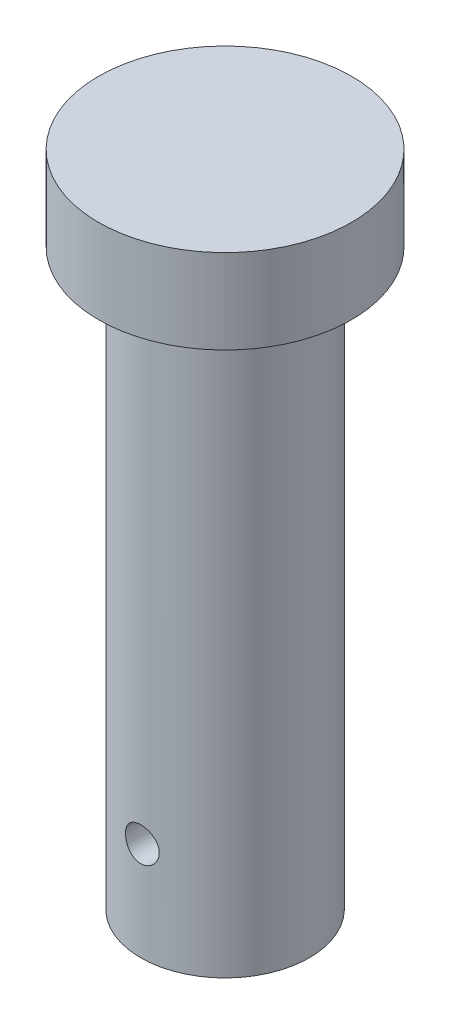
SolidWorks part; units mm, degrees
ref_plane "Front Plane" through (0, 0, 0) normal (0, 0, 1) x (1, 0, 0)
ref_plane "Top Plane" through (0, 0, 0) normal (0, 1, 0) x (1, 0, 0)
ref_plane "Right Plane" through (0, 0, 0) normal (1, 0, 0) x (0, 0, -1)
sketch "Sketch1" plane through (0, 0, 0) normal (0, 0, 1) x (1, 0, 0)
  line L0 (0, 0) -> (15, 0)
  line L1 (15, 0) -> (15, 102)
  line L2 (15, 102) -> (22.5, 102)
  line L3 (22.5, 102) -> (22.5, 117)
  line L4 (22.5, 117) -> (0, 117)
  line L5 (0, 117) -> (0, 0)
  dimension "D1" = 15
  dimension "D2" = 102
  dimension "D3" = 15
  dimension "D4" = 22.5
revolve "Revolve1" add sketch "Sketch1" angle 360 about L5
sketch "Sketch2" plane through (0, 0, 0) normal (0, 0, 1) x (1, 0, 0)
  circle A0 centre (0, 17.5) radius 3
  dimension "D1" = 6
  dimension "D2" = 17.5
extrude "Cut-Extrude1" cut sketch "Sketch2" against normal through all both and the other way through all
